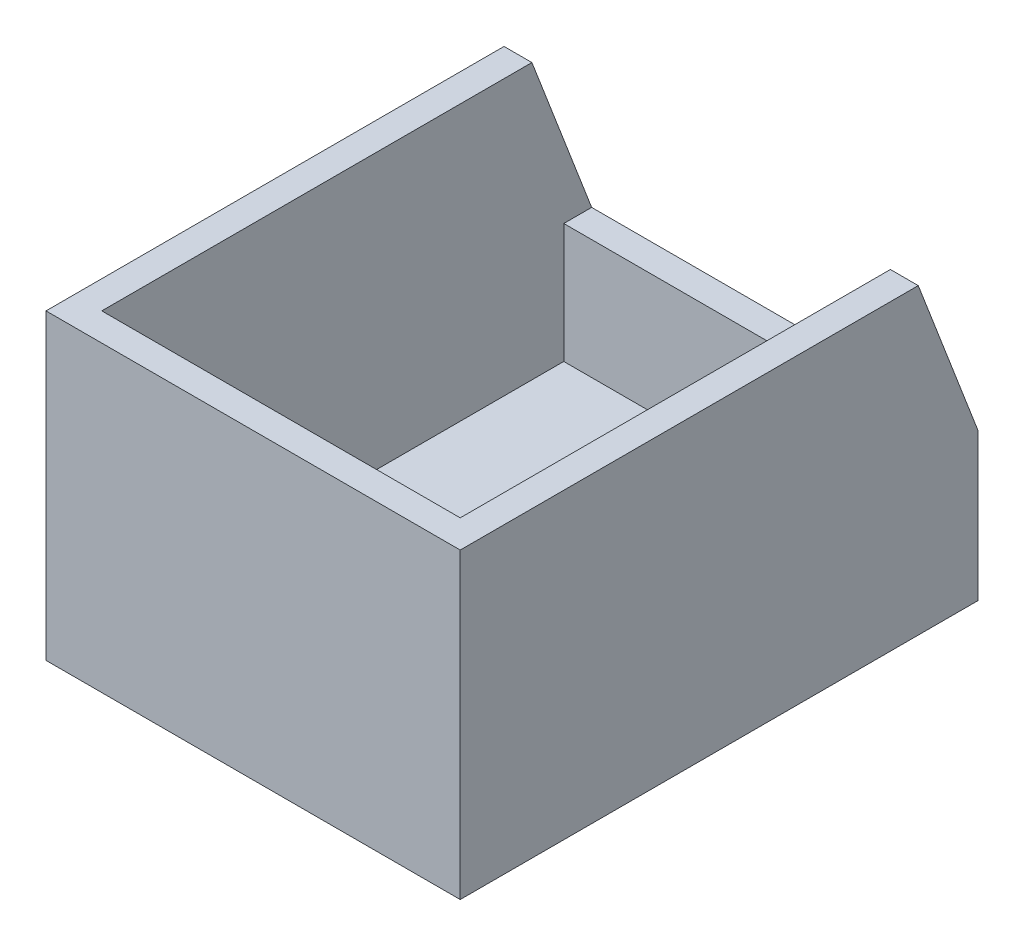
SolidWorks part; units mm, degrees
material "Custom Plastic"
ref_plane "Front Plane" through (0, 0, 0) normal (0, 0, 1) x (1, 0, 0)
ref_plane "Top Plane" through (0, 0, 0) normal (0, 1, 0) x (1, 0, 0)
ref_plane "Right Plane" through (0, 0, 0) normal (1, 0, 0) x (0, 0, -1)
sketch "Sketch1" plane through (0, 0, 0) normal (1, 0, 0) x (0, 0, -1)
  line L0 (0, 0) -> (130, 0)
  line L1 (130, 0) -> (130, 37)
  line L2 (130, 37) -> (115, 76)
  line L3 (115, 76) -> (0, 76)
  line L4 (0, 76) -> (0, 0)
  dimension "D1" = 130
  dimension "D2" = 37
  dimension "D3" = 76
  dimension "D4" = 115
extrude "Boss-Extrude1" add sketch "Sketch1" along normal blind 104
shell "Shell1" thickness 7
sketch "Sketch3" plane through (0, 0, -123) normal (0, 0, 1) x (1, 0, 0)
  line L0 (97, 7) -> (97, 55.2) construction
  line L3 (7, 55.2) -> (97, 55.2)
  line L4 (7, 55.2) -> (7, 37)
  line L5 (7, 37) -> (97, 37)
  line L6 (97, 55.2) -> (97, 37)
  dimension "D1" = 18.2
extrude "Cut-Extrude1" cut sketch "Sketch3" against normal blind 104
